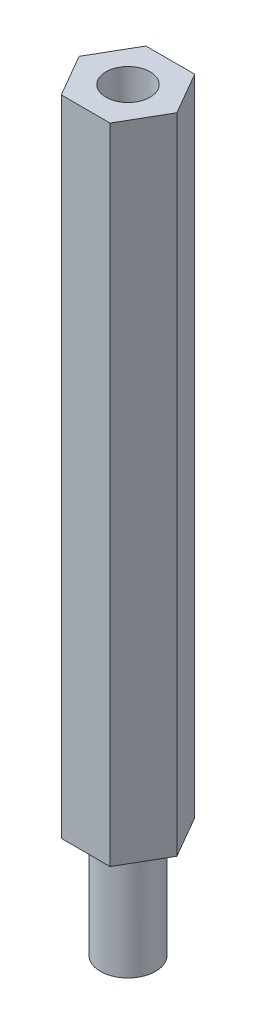
SolidWorks part; units mm, degrees
other "Markup1"
sketch "Sketch2" plane through (2.6558, 40, 2.3) normal (0.3825, 0.9065, 0.1787) x (0.7461, -0.1889, -0.6385)
ref_plane "Front Plane" through (0, 0, 0) normal (0, 0, 1) x (1, 0, 0)
ref_plane "Top Plane" through (0, 0, 0) normal (0, 1, 0) x (1, 0, 0)
ref_plane "Right Plane" through (0, 0, 0) normal (1, 0, 0) x (0, 0, -1)
sketch "Sketch1" plane through (0, 0, 0) normal (0, 1, 0) x (1, 0, 0)
  line L1 (2.6558, 0) -> (1.3279, 2.3)
  line L2 (1.3279, 2.3) -> (-1.3279, 2.3)
  line L3 (-1.3279, 2.3) -> (-2.6558, 0)
  line L4 (-2.6558, 0) -> (-1.3279, -2.3)
  line L5 (-1.3279, -2.3) -> (1.3279, -2.3)
  line L6 (1.3279, -2.3) -> (2.6558, 0)
  circle A0 centre (0, 0) radius 2.3 construction
  circle A2 centre (0, 0) radius 1.2
  dimension "D2" = 1.2
  dimension "D1" = 4.6
extrude "Boss-Extrude1" add sketch "Sketch1" along normal blind 35
sketch "Sketch3" plane through (0, 0, 0) normal (0, -1, 0) x (-1, 0, 0)
  circle A0 centre (0, 0) radius 1.5
  dimension "D1" = 3
extrude "Boss-Extrude2" add sketch "Sketch3" along normal blind 6
